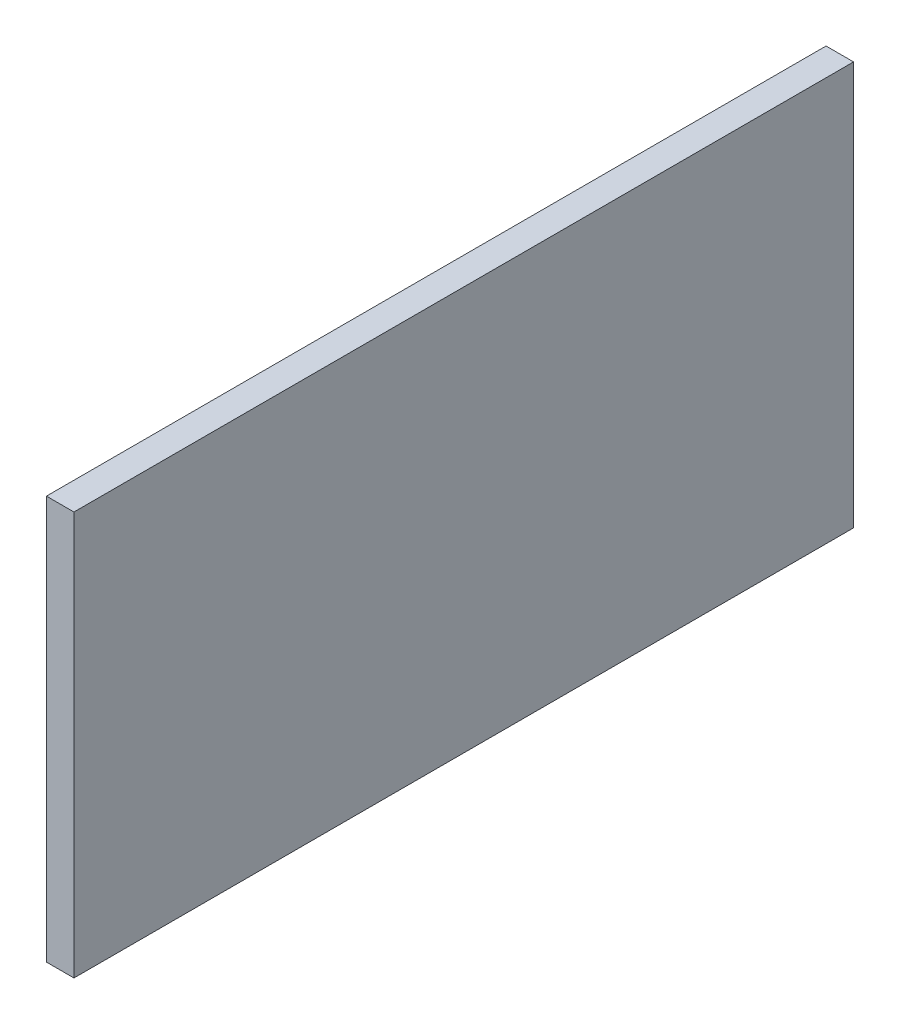
SolidWorks part; units mm, degrees
material "ABS"
ref_plane "Front Plane" through (0, 0, 0) normal (0, 0, 1) x (1, 0, 0)
ref_plane "Top Plane" through (0, 0, 0) normal (0, 1, 0) x (1, 0, 0)
ref_plane "Right Plane" through (0, 0, 0) normal (1, 0, 0) x (0, 0, -1)
sketch "Sketch1" plane through (0, 0, 0) normal (1, 0, 0) x (0, 0, -1)
  line L1 (-47, 2) -> (38, 2)
  line L2 (-47, 2) -> (-47, 46)
  line L3 (-47, 46) -> (38, 46)
  line L4 (38, 2) -> (38, 46)
extrude "Boss-Extrude1" add sketch "Sketch1" along normal mid plane 3 from offset 123.5
sketch "Sketch2" plane through (0, 0, 0) normal (0, 0, 1) x (1, 0, 0)
  circle A0 centre (108.2, 18.5) radius 6.5
extrude "Boss-Extrude2" add sketch "Sketch2" along normal mid plane 4.2 from offset 14.1
sketch "Sketch3" plane through (0, 0, 0) normal (0, 0, 1) x (1, 0, 0)
  line L1 (108.2, 12) -> (122.5, 12)
  line L2 (108.2, 12) -> (108.2, 25)
  line L3 (108.2, 25) -> (122.5, 25)
  line L4 (122.5, 12) -> (122.5, 25)
  circle A0 centre (108.2, 18.5) radius 6.5 construction
extrude "Boss-Extrude3" add sketch "Sketch3" along normal mid plane 4.2 from offset 14.1
sketch "Sketch4" plane through (0, 0, 0) normal (0, 0, 1) x (1, 0, 0)
  circle A0 centre (108.2, 18.5) radius 3.55
extrude "Cut-Extrude1" cut sketch "Sketch4" against normal mid plane 4.2 from offset 14.1
sketch "Sketch5" plane through (0, 0, 0) normal (0, 0, 1) x (1, 0, 0)
  line L0 (108.2, 14.95) -> (120.9, 16.0967)
  line L1 (120.9, 16.0967) -> (120.9, 20.9033)
  line L2 (120.9, 20.9033) -> (108.2, 22.05)
  line L3 (108.2, 22.05) -> (108.2, 14.95)
  circle A0 centre (108.2, 18.5) radius 3.55 construction
extrude "Cut-Extrude2" cut sketch "Sketch5" against normal mid plane 4.2 from offset 14.1
sketch "Sketch6" plane through (0, 0, 0) normal (0, 0, 1) x (1, 0, 0)
  circle A0 centre (108.2, 18.5) radius 6.5
extrude "Boss-Extrude4" add sketch "Sketch6" along normal mid plane 3 from offset 24.5
sketch "Sketch7" plane through (0, 0, 0) normal (0, 0, 1) x (1, 0, 0)
  line L1 (108.2, 12) -> (122.5, 12)
  line L2 (108.2, 12) -> (108.2, 25)
  line L3 (108.2, 25) -> (122.5, 25)
  line L4 (122.5, 12) -> (122.5, 25)
extrude "Boss-Extrude5" add sketch "Sketch7" along normal mid plane 3 from offset 24.5
sketch "Sketch8" plane through (0, 0, 0) normal (0, 0, 1) x (1, 0, 0)
  circle A0 centre (108.2, 18.5) radius 2.95
extrude "Cut-Extrude3" cut sketch "Sketch8" against normal mid plane 3 from offset 24.5
